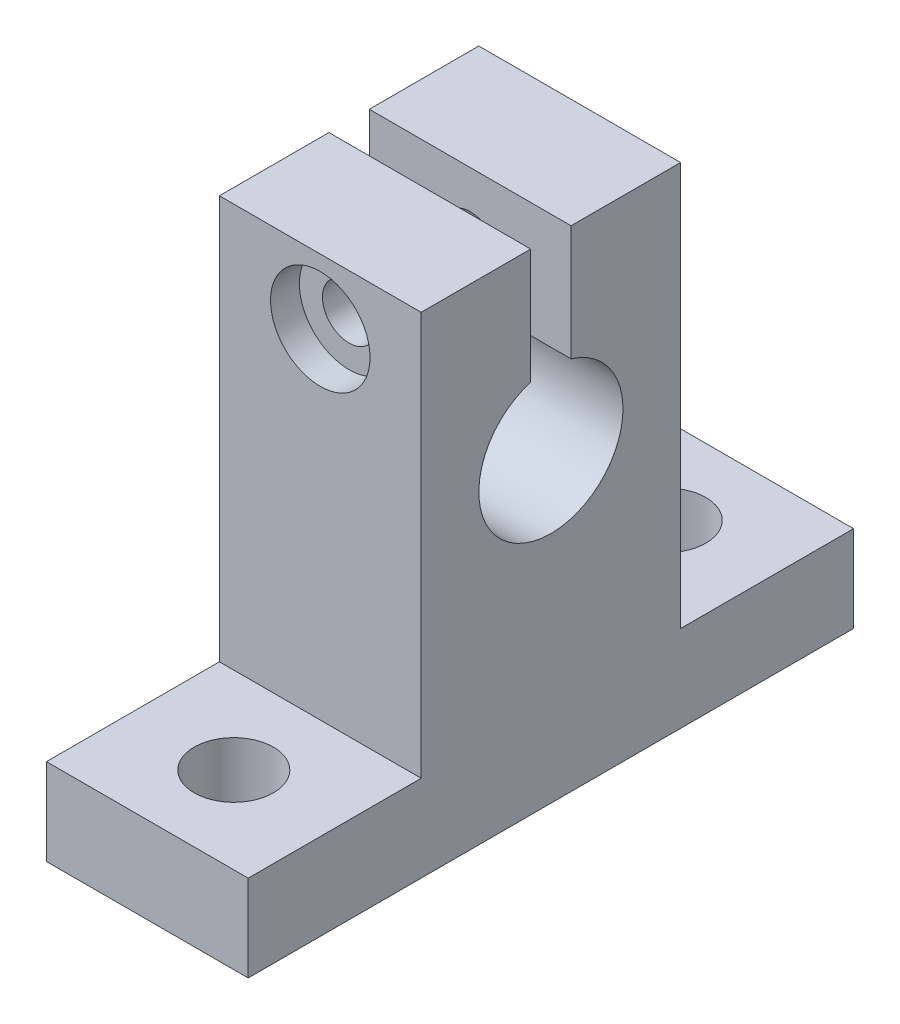
SolidWorks part; units mm, degrees
material "1060-H18"
ref_plane "Front Plane" through (0, 0, 0) normal (0, 0, 1) x (1, 0, 0)
ref_plane "Top Plane" through (0, 0, 0) normal (0, 1, 0) x (1, 0, 0)
ref_plane "Right Plane" through (0, 0, 0) normal (1, 0, 0) x (0, 0, -1)
sketch "Sketch2" plane through (0, 0, 0) normal (1, 0, 0) x (0, 0, -1)
  line L0 (0, 0) -> (42, 0)
  line L1 (42, 0) -> (42, 6)
  line L2 (42, 6) -> (30, 6)
  line L3 (30, 6) -> (30, 34)
  line L4 (30, 34) -> (22.4, 34)
  line L5 (22.4, 34) -> (22.4, 26)
  line L6 (0, 0) -> (0, 6)
  line L7 (0, 6) -> (12, 6)
  line L8 (12, 6) -> (12, 34)
  line L9 (12, 34) -> (19.6, 34)
  line L10 (19.6, 34) -> (19.6, 26)
  arc A0 (19.6, 26) -> (22.4, 26) centre (21, 21.2) ccw
  point P16 (21, 0)
  dimension "D7" = 5
  dimension "D1" = 42
  dimension "D2" = 6
  dimension "D3" = 12
  dimension "D4" = 28
  dimension "D5" = 7.6
  dimension "D6" = 8
extrude "Boss-Extrude1" add sketch "Sketch2" along normal blind 14
sketch "Sketch3" plane through (0, 0, -30) normal (0, 0, -1) x (-1, 0, 0)
  line L0 (-7, 34) -> (-7, 15.7512) construction
  line L1 (-14, 34) -> (0, 34) construction
  circle A0 centre (-7, 29.5) radius 1.85
  dimension "D2" = 3.7
  dimension "D1" = 4.5
extrude "Cut-Extrude1" cut sketch "Sketch3" against normal through all
sketch "Sketch4" plane through (0, 6, 0) normal (0, 1, 0) x (1, 0, 0)
  line L0 (7, 42) -> (7, 0) construction
  line L1 (14, 42) -> (0, 42) construction
  line L2 (14, 0) -> (0, 0) construction
  line L3 (14, 6) -> (0, 6) construction
  line L4 (14, 12) -> (14, 0) construction
  line L5 (0, 12) -> (0, 0) construction
  line L6 (14, 36) -> (0, 36) construction
  line L7 (14, 42) -> (14, 30) construction
  line L8 (0, 42) -> (0, 30) construction
  circle A0 centre (7, 36) radius 2.75
  circle A1 centre (7, 6) radius 2.75
  dimension "D1" = 5.5
extrude "Cut-Extrude2" cut sketch "Sketch4" against normal through all
sketch "Sketch5" plane through (0, 0, -12) normal (0, 0, 1) x (1, 0, 0)
  circle A0 centre (7, 29.5) radius 3.4525
extrude "Cut-Extrude3" cut sketch "Sketch5" against normal blind 2
